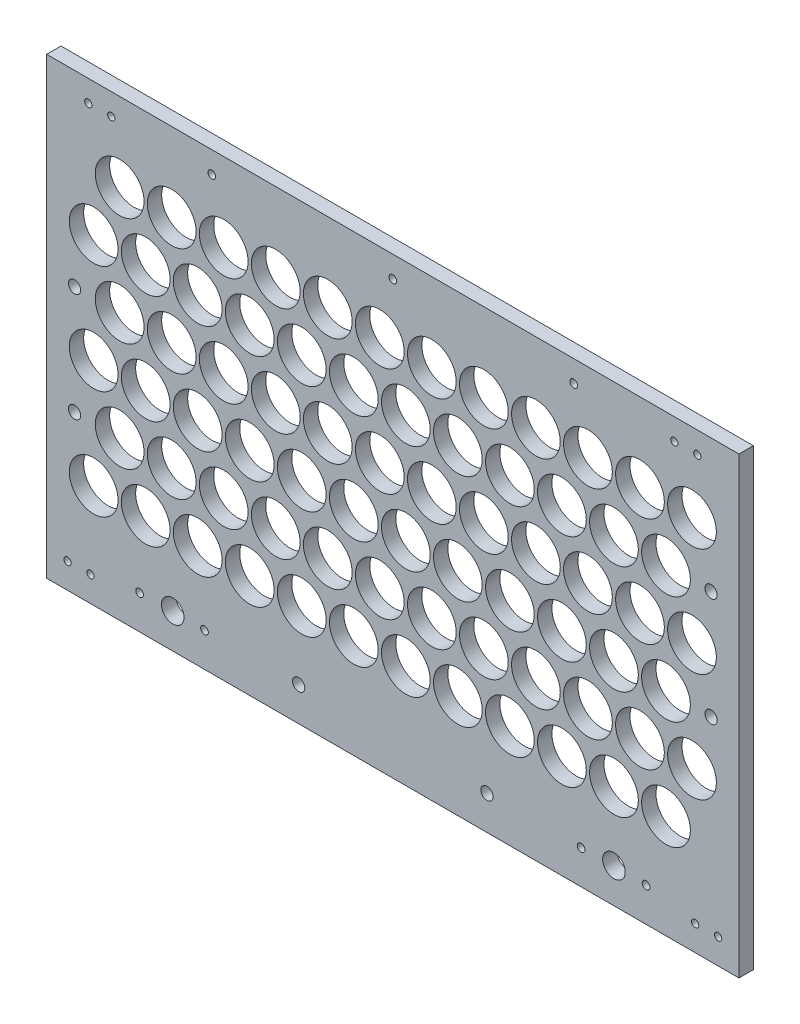
SolidWorks part; units mm, degrees
material "ABS"
ref_plane "X-Y Datum" through (0, 0, 0) normal (0, 0, 1) x (1, 0, 0)
ref_plane "X-Z Datum" through (0, 0, 0) normal (0, 1, 0) x (1, 0, 0)
ref_plane "Y-Z Datum" through (0, 0, 0) normal (1, 0, 0) x (0, 0, -1)
sketch "Sketch1" plane through (0, 0, 0) normal (0, 0, 1) x (1, 0, 0)
  line L1 (-143.025, 70.775) -> (143.025, 70.775)
  line L2 (-143.025, 70.775) -> (-143.025, -70.775)
  line L3 (-143.025, -70.775) -> (143.025, -70.775)
  line L4 (143.025, 70.775) -> (143.025, -70.775)
  line L5 (-143.025, 70.775) -> (143.025, -70.775) construction
  line L6 (-143.025, -70.775) -> (143.025, 70.775) construction
  line L13 (-153.025, -105.775) -> (153.025, -105.775)
  line L14 (-153.025, 91.65) -> (153.025, 91.65)
  line L15 (-153.025, 91.65) -> (-153.025, -105.775)
  line L16 (153.025, 91.65) -> (153.025, -105.775)
  line L17 (153.025, 70.775) -> (153.025, -70.775) construction
  line L18 (-143.025, 91.65) -> (143.025, 91.65) construction
  line L19 (-143.025, -105.775) -> (143.025, -105.775) construction
  line L20 (-153.025, 70.775) -> (-153.025, -70.775) construction
  line L21 (-132.25, -60) -> (-109.25, -60) construction
  circle A0 centre (-132.25, -60) radius 10.775
  circle A1 centre (-109.25, -60) radius 10.775 construction
  circle A2 centre (-120.75, -36) radius 10.775
  point P0 (0, 0)
  point P16 (-120.75, -60)
  dimension "D1" = 21.55
  dimension "D2" = 23
  dimension "D3" = 24
  dimension "D5" = 141.55
  dimension "D6" = 286.05
  dimension "D7" = 35
  dimension "D8" = 20.875
  dimension "D9" = 10
  dimension "D10" = 10
extrude "Boss-Extrude1" add sketch "Sketch1" along normal blind 6.35
sketch "Sketch3" plane through (0, 0, 6.35) normal (0, 0, 1) x (1, 0, 0)
  line L4 (143.025, 70.775) -> (-143.025, 70.775)
  line L5 (143.025, -70.775) -> (143.025, 70.775)
  line L6 (-143.025, -70.775) -> (143.025, -70.775)
  line L7 (-143.025, 70.775) -> (-143.025, -70.775)
  line L8 (143.025, 70.775) -> (-143.025, 70.775)
  line L9 (143.025, -70.775) -> (143.025, 70.775)
  line L10 (-143.025, -70.775) -> (143.025, -70.775)
  line L11 (-143.025, 70.775) -> (-143.025, -70.775)
  circle A1 centre (-120.75, -36) radius 10.775
  circle A2 centre (-120.75, -36) radius 10.775
  circle A3 centre (-132.25, -60) radius 10.775
  circle A4 centre (-132.25, -60) radius 10.775
  dimension "D1" = 0
  dimension "D2" = 0
  dimension "D3" = 0
extrude "Cut-Extrude1" cut sketch "Sketch3" against normal through all contours A4
sketch "Sketch4" plane through (0, 0, 6.35) normal (0, 0, 1) x (1, 0, 0)
  line L4 (143.025, 70.775) -> (-143.025, 70.775)
  line L5 (143.025, -70.775) -> (143.025, 70.775)
  line L6 (-143.025, -70.775) -> (143.025, -70.775)
  line L7 (-143.025, 70.775) -> (-143.025, -70.775)
  line L8 (143.025, 70.775) -> (-143.025, 70.775)
  line L9 (143.025, -70.775) -> (143.025, 70.775)
  line L10 (-143.025, -70.775) -> (143.025, -70.775)
  line L11 (-143.025, 70.775) -> (-143.025, -70.775)
  circle A1 centre (-120.75, -36) radius 10.775
  circle A2 centre (-120.75, -36) radius 10.775
  circle A3 centre (-132.25, -60) radius 10.775
  circle A4 centre (-132.25, -60) radius 10.775
  dimension "D1" = 0
  dimension "D2" = 0
  dimension "D3" = 0
extrude "Cut-Extrude2" cut sketch "Sketch4" against normal through all contours A2
pattern_linear "LPattern1" count 12 spacing 23 along (1, 0, 0) of "Cut-Extrude1", "Cut-Extrude2"
pattern_linear "LPattern2" count 3 spacing 48 along (0, 1, 0) of "LPattern1", "Cut-Extrude1", "Cut-Extrude2"
sketch "Sketch5" plane through (0, 0, 0) normal (0, 0, -1) x (-1, 0, 0)
  circle A0 centre (-97.75, -90.3965) radius 2 construction
  circle A1 centre (-97.75, -90.3965) radius 2 construction
  circle A2 centre (-97.75, -90.3965) radius 5
  circle A3 centre (97.288, -90.3965) radius 5
  point P4 (97.288, -90.3965)
  dimension "D1" = 10
extrude "Cut-Extrude3" cut sketch "Sketch5" against normal through all
sketch "Sketch7" plane through (0, 0, 0) normal (0, 0, -1) x (-1, 0, 0)
  line L0 (0, 3.4925) -> (0, -3.4925) construction
  point P0 (-111.94, -90.775)
  point P1 (-133.6575, -94.6)
  point P3 (-143.8175, -94.6)
  point P5 (-124.45, 85.3)
  point P7 (-134.61, 85.3)
  point P9 (80, 85.3)
  point P11 (0, 85.3)
  point P13 (-80, 85.3)
  point P15 (124.45, 85.3)
  point P17 (134.61, 85.3)
  point P19 (143.8175, -94.6)
  point P21 (133.6575, -94.6)
  point P23 (-83.25, -90.775)
  point P28 (83.25, -90.775)
  point P29 (111.94, -90.775)
hole_wizard "M3 Clearance Hole1" positions "Sketch8" profile "Sketch9" hole size "M3" standard "ANSI Metric" end condition through all
sketch "Sketch8" plane through (0, 0, 0) normal (0, 0, -1) x (-1, 0, 0)
  point P0 (-111.94, -90.775)
  point P3 (80, 85.3)
  point P6 (0, 85.3)
  point P9 (-80, 85.3)
  point P13 (-83.25, -90.775)
  point P17 (111.94, -90.775)
  point P20 (83.25, -90.775)
sketch "Sketch9" plane through (111.94, -90.775, 0) normal (1, 0, 0) x (0, 1, 0)
  line L0 (0, 0) -> (0, 6.35)
  line L1 (0, 6.35) -> (1.7, 6.35)
  line L2 (1.7, 6.35) -> (1.7, 0)
  line L5 (1.7, 0) -> (0, 0)
  line L11 (0, -6.35) -> (0, 107.95) construction
  dimension "Thru Hole Dia." = 3.4
  dimension "Thru Hole Depth" = 6.35
hole_wizard "M3 Clearance Hole2" positions "Sketch10" profile "Sketch11" hole size "M3" standard "ANSI Metric" end condition through all
sketch "Sketch10" plane through (0, 0, 0) normal (0, 0, -1) x (-1, 0, 0)
  point P0 (-143.8175, -94.6)
  point P3 (-133.6575, -94.6)
  point P6 (-134.61, 85.3)
  point P9 (-124.45, 85.3)
  point P12 (124.45, 85.3)
  point P15 (134.61, 85.3)
  point P18 (133.6575, -94.6)
  point P21 (143.8175, -94.6)
sketch "Sketch11" plane through (143.8175, -94.6, 0) normal (1, 0, 0) x (0, 1, 0)
  line L0 (0, 0) -> (0, 6.35)
  line L1 (0, 6.35) -> (1.6, 6.35)
  line L2 (1.6, 6.35) -> (1.6, 0)
  line L5 (1.6, 0) -> (0, 0)
  line L11 (0, -6.35) -> (0, 107.95) construction
  dimension "Thru Hole Dia." = 3.2
  dimension "Thru Hole Depth" = 6.35
sketch "Sketch12" plane through (0, 0, 0) normal (0, 0, -1) x (-1, 0, 0)
  line L0 (83.25, -90.775) -> (-83.25, -90.775) construction
  line L1 (0, -98.7518) -> (0, -82.7982) construction
  line L2 (83.25, -90.775) -> (0, -90.775) construction
  circle A0 centre (41.625, -90.775) radius 2.7
  circle A1 centre (-41.625, -90.775) radius 2.7
  circle A2 centre (140.6875, -36) radius 2.7
  circle A3 centre (-140.6875, 36) radius 2.7
  circle A4 centre (140.6875, 12) radius 2.7
  circle A5 centre (-140.6875, -12) radius 2.7
  point P0 (140.6875, 60)
  point P1 (140.6875, 12)
  point P3 (140.6875, -36)
  point P5 (-140.6875, 36)
  point P7 (-140.6875, -12)
  point P9 (-140.6875, -60)
  point P16 (41.625, -90.775)
  point P20 (0, -90.775)
  dimension "D1" = 5.4
extrude "Cut-Extrude4" cut sketch "Sketch12" against normal through all
sketch "Sketch13" plane through (0, 91.65, 0) normal (0, 1, 0) x (1, 0, 0)
  line L4 (153.025, 0) -> (-153.025, 0)
  line L5 (-153.025, 0) -> (-153.025, -6.35)
  line L6 (-153.025, -6.35) -> (153.025, -6.35)
  line L7 (153.025, -6.35) -> (153.025, 0)
  line L8 (153.025, 0) -> (-153.025, 0)
  line L9 (-153.025, 0) -> (-153.025, -6.35)
  line L10 (-153.025, -6.35) -> (153.025, -6.35)
  line L11 (153.025, -6.35) -> (153.025, 0)
  dimension "D1" = 0
extrude "Boss-Extrude2" add sketch "Sketch13" along normal blind 3.175
